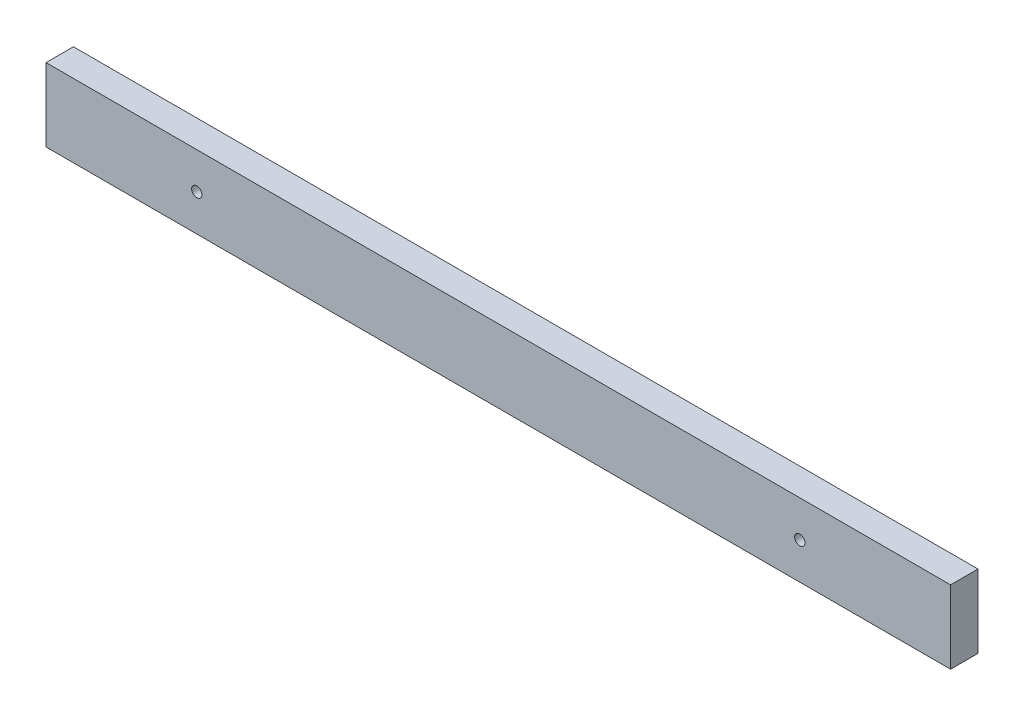
SolidWorks part; units mm, degrees
ref_plane "Front Plane" through (0, 0, 0) normal (0, 0, 1) x (1, 0, 0)
ref_plane "Top Plane" through (0, 0, 0) normal (0, 1, 0) x (1, 0, 0)
ref_plane "Right Plane" through (0, 0, 0) normal (1, 0, 0) x (0, 0, -1)
sketch "Sketch1" plane through (0, 0, 0) normal (0, 1, 0) x (1, 0, 0)
  line L0 (-99, 3) -> (99, 3)
  line L1 (-99, 3) -> (-99, -3)
  line L2 (-99, -3) -> (99, -3)
  line L3 (99, 3) -> (99, -3)
  line L4 (-99, 3) -> (99, -3) construction
  line L5 (-99, -3) -> (99, 3) construction
  point P4 (0, 0)
  dimension "D1" = 6
  dimension "D2" = 198
extrude "Boss-Extrude1" add sketch "Sketch1" along normal blind 16
sketch "Sketch2" plane through (0, 0, 3) normal (0, 0, 1) x (1, 0, 0)
  line L0 (-99, 8) -> (-66, 8) construction
  line L1 (-99, 16) -> (-99, 0) construction
  line L2 (-66, 8) -> (-33, 8) construction
  line L3 (-33, 8) -> (0, 8) construction
  line L4 (0, 8) -> (33, 8) construction
  line L5 (33, 8) -> (66, 8) construction
  line L6 (66, 8) -> (99, 8) construction
  line L7 (99, 16) -> (99, 0) construction
  line L8 (0, 8) -> (0, 0) construction
  circle A0 centre (-66, 8) radius 1.125
  circle A1 centre (0, 8) radius 1.125 construction
  circle A2 centre (66, 8) radius 1.125
  dimension "D1" = 2.25
extrude "Cut-Extrude1" cut sketch "Sketch2" against normal blind 10
